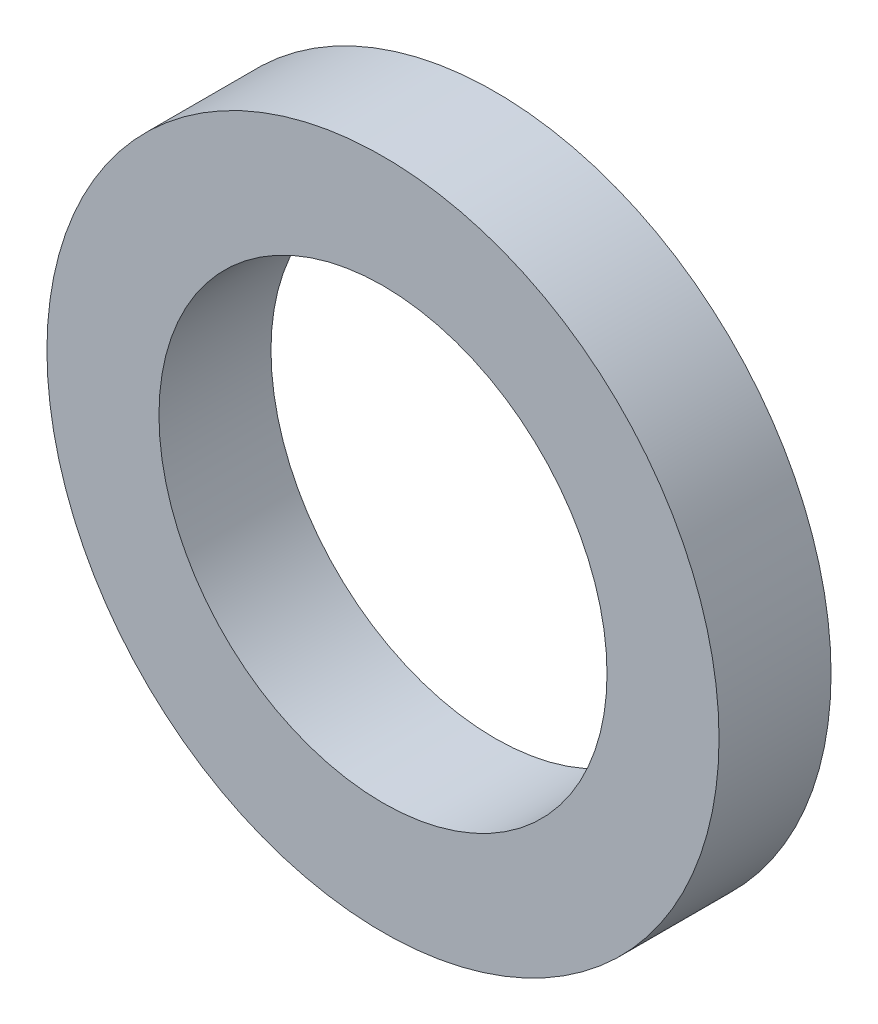
SolidWorks part; units mm, degrees
ref_plane "Front Plane" through (0, 0, 0) normal (0, 0, 1) x (1, 0, 0)
ref_plane "Top Plane" through (0, 0, 0) normal (0, 1, 0) x (1, 0, 0)
ref_plane "Right Plane" through (0, 0, 0) normal (1, 0, 0) x (0, 0, -1)
sketch "Sketch1" plane through (0, 0, 0) normal (0, 0, 1) x (1, 0, 0)
  circle A0 centre (0, 0) radius 10
  circle A1 centre (0, 0) radius 15
  dimension "D1" = 20
  dimension "D2" = 30
extrude "Boss-Extrude1" add sketch "Sketch1" along normal blind 5
